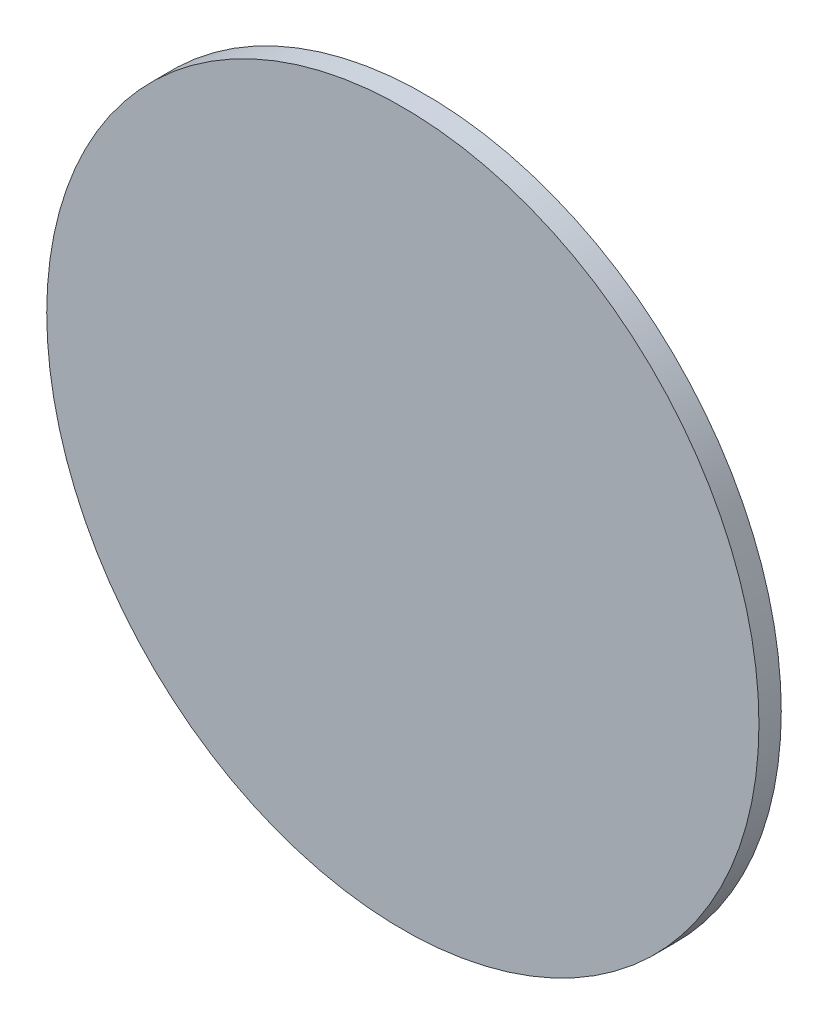
SolidWorks part; units mm, degrees
ref_plane "Front Plane" through (0, 0, 0) normal (0, 0, 1) x (1, 0, 0)
ref_plane "Top Plane" through (0, 0, 0) normal (0, 1, 0) x (1, 0, 0)
ref_plane "Right Plane" through (0, 0, 0) normal (1, 0, 0) x (0, 0, -1)
sketch "Sketch1" plane through (0, 0, 0) normal (0, 0, 1) x (1, 0, 0)
  circle A0 centre (0, 0) radius 15.95
  dimension "D1" = 31.9
extrude "Extrude1" add sketch "Sketch1" along normal blind 1
